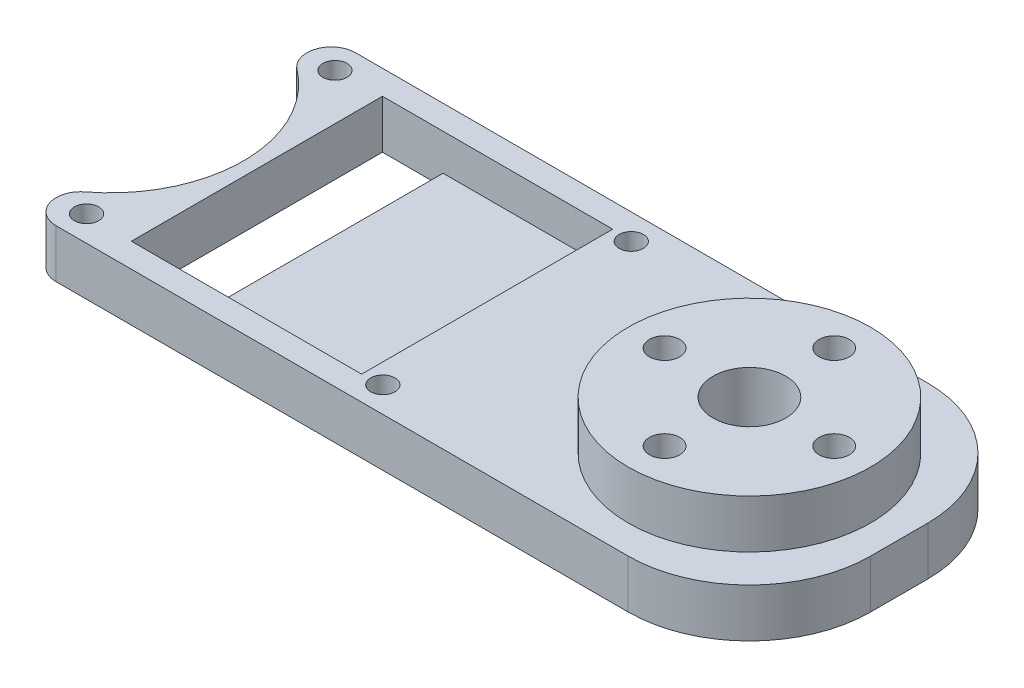
SolidWorks part; units mm, degrees
ref_plane "前视基准面" through (0, 0, 0) normal (0, 0, 1) x (1, 0, 0)
ref_plane "上视基准面" through (0, 0, 0) normal (0, 1, 0) x (1, 0, 0)
ref_plane "右视基准面" through (0, 0, 0) normal (1, 0, 0) x (0, 0, -1)
other "Configuration Table"
ref_plane "基准面1" through (0, 0, 0) normal (0, 1, 0) x (1, 0, 0)
sketch "草图1" plane through (0, 0, 0) normal (0, 1, 0) x (1, 0, 0)
  line L0 (6.61, -12.36) -> (9.61, -12.36)
  line L1 (-32.61, -12.36) -> (6.61, -12.36)
  line L2 (-35.61, -9.36) -> (-35.61, 9.36)
  line L3 (-32.61, 12.36) -> (6.61, 12.36)
  line L4 (9.61, -9.36) -> (9.61, 9.36)
  line L5 (9.61, -12.36) -> (9.61, -9.36)
  line L6 (6.61, 12.36) -> (9.61, 12.36)
  line L7 (9.61, 12.36) -> (9.61, 9.36)
  arc A1 (-32.61, 12.36) -> (-35.61, 9.36) centre (-32.61, 9.36) ccw
  arc A2 (-35.61, -9.36) -> (-32.61, -12.36) centre (-32.61, -9.36) ccw
extrude "凸台-拉伸1" add sketch "草图1" along normal blind 4
sketch "草图2" plane through (0, 0, 0) normal (0, 1, 0) x (1, 0, 0)
  circle A0 centre (7.25, -10.25) radius 1
  circle A1 centre (7.25, 10.25) radius 1
  circle A2 centre (-17.2, -10.25) radius 1
  circle A3 centre (-17.2, 10.25) radius 1
  dimension "D1" = 2
  dimension "D2" = 2
  dimension "D3" = 2
  dimension "D4" = 2
extrude "切除-拉伸1" cut sketch "草图2" against normal through all and the other way through all
sketch "草图3" plane through (0, 4, 0) normal (0, 1, 0) x (1, 0, 0)
  line L0 (9.61, 12.36) -> (-32.61, 12.36) construction
  line L1 (-8.39, -10.36) -> (5.61, -10.36)
  line L2 (-8.39, -10.36) -> (-8.39, 10.36)
  line L3 (-8.39, 10.36) -> (5.61, 10.36)
  line L4 (5.61, -10.36) -> (5.61, 10.36)
  line L9 (9.61, -12.36) -> (9.61, 12.36) construction
  line L10 (-32.61, -12.36) -> (9.61, -12.36) construction
  dimension "D1" = 2
  dimension "D2" = 4
  dimension "D3" = 2
  dimension "D4" = 14
extrude "切除-拉伸3" cut sketch "草图3" against normal blind 3
sketch "草图5" plane through (0, 4, 0) normal (0, 1, 0) x (1, 0, 0)
  line L0 (9.61, 12.36) -> (-32.61, 12.36) construction
  line L1 (-13.39, 10.36) -> (-8.39, 10.36)
  line L2 (-13.39, 10.36) -> (-13.39, -10.36)
  line L3 (-13.39, -10.36) -> (-8.39, -10.36)
  line L4 (-8.39, 10.36) -> (-8.39, -10.36)
  line L5 (-8.39, 10.36) -> (-8.39, -10.36) construction
  line L6 (-32.61, -12.36) -> (9.61, -12.36) construction
  dimension "D1" = 2
  dimension "D2" = 0
  dimension "D3" = 2
  dimension "D4" = 5
extrude "切除-拉伸4" cut sketch "草图5" against normal blind 4
sketch "草图6" plane through (0, 4, 0) normal (0, 1, 0) x (1, 0, 0)
  line L0 (9.61, -12.36) -> (9.61, 12.36) construction
  circle A0 centre (-25.5, 0) radius 11
  dimension "D2" = 22
  dimension "D1" = 35.11
sketch "草图13" plane through (9.61, 0, 0) normal (1, 0, 0) x (0, 0, -1)
  line L4 (-12.36, 0) -> (12.36, 0)
  line L5 (12.36, 0) -> (12.36, 4)
  line L6 (12.36, 4) -> (-12.36, 4)
  line L7 (-12.36, 4) -> (-12.36, 0)
  line L8 (-12.36, 0) -> (12.36, 0)
  line L9 (12.36, 0) -> (12.36, 4)
  line L10 (12.36, 4) -> (-12.36, 4)
  line L11 (-12.36, 4) -> (-12.36, 0)
  dimension "D1" = 0
extrude "凸台-拉伸5" add sketch "草图13" along normal blind 30
sketch "草图15" plane through (0, 4, 0) normal (0, 1, 0) x (1, 0, 0)
  line L0 (39.61, 12.36) -> (-32.61, 12.36) construction
  line L1 (39.61, 12.36) -> (39.61, -12.36) construction
  circle A0 centre (27.25, 0) radius 10
  point P6 (-31.8688, 35.6649)
  dimension "D1" = 20
  dimension "D2" = 12.36
  dimension "D3" = 12.36
extrude "凸台-拉伸6" add sketch "草图15" along normal blind 4
sketch "草图14" plane through (0, 4, 0) normal (0, 1, 0) x (1, 0, 0)
  line L0 (39.61, 12.36) -> (39.61, -12.36) construction
  line L1 (39.61, 12.36) -> (-32.61, 12.36) construction
  circle A0 centre (27.25, 0) radius 10
  circle A1 centre (27.25, -7) radius 1.25
  circle A2 centre (34.25, 0) radius 1.25
  circle A3 centre (27.25, 7) radius 1.25
  circle A4 centre (20.25, 0) radius 1.25
  circle A5 centre (27.25, 0) radius 4.5
  point P4 (39.61, 0)
  point P16 (0, 0)
  dimension "D1" = 20
  dimension "D2" = 12.36
  dimension "D3" = 12.36
  dimension "D4" = 9
  dimension "D5" = 2.5
  dimension "D6" = 2.5
  dimension "D7" = 2.5
  dimension "D8" = 2.5
  dimension "D9" = 14
  dimension "D10" = 14
  dimension "D11" = 7
  dimension "D12" = 7
  dimension "D13" = 7
  dimension "D14" = 5.36
  dimension "D15" = 5.36
  dimension "D16" = 12.36
extrude "切除-拉伸7" cut sketch "草图14" along normal mid plane 8 contours A1 | A4 | A2 | A3
fillet "圆角1" radius 10 1 edges at (39.61, 2, -12.36)
fillet "圆角2" radius 10 1 edges at (39.61, 2, 12.36)
extrude "切除-拉伸9" cut sketch "草图6" against normal blind 4
sketch "草图17" plane through (-35.61, 0, 0) normal (-1, 0, 0) x (0, 0, 1)
  line L0 (-12.36, 4) -> (-12.36, 0) construction
  line L1 (-12.36, 4) -> (12.36, 4)
  line L2 (-12.36, 4) -> (-12.36, 0)
  line L3 (-12.36, 0) -> (12.36, 0)
  line L4 (12.36, 4) -> (12.36, 0)
  line L5 (-9.36, 4) -> (-4.3345, 4) construction
  line L6 (13.596, 0) -> (-13.596, 0) construction
  line L7 (12.36, 4) -> (12.36, 0) construction
  dimension "D1" = 0
  dimension "D2" = 0
  dimension "D3" = 0
extrude "切除-拉伸10" cut sketch "草图17" against normal blind 16
fillet "圆角3" radius 2 1 edges at (-19.61, 2, 12.36)
fillet "圆角4" radius 2 1 edges at (-19.61, 2, -12.36)
fillet "圆角5" radius 2 1 edges at (-19.61, 2, -9.2902)
fillet "圆角6" radius 2 1 edges at (-19.61, 2, 9.2902)
sketch "草图18" plane through (0, 8, 0) normal (0, 1, 0) x (1, 0, 0)
  circle A0 centre (27.25, 0) radius 3
  dimension "D1" = 6
extrude "切除-拉伸11" cut sketch "草图18" against normal blind 13
